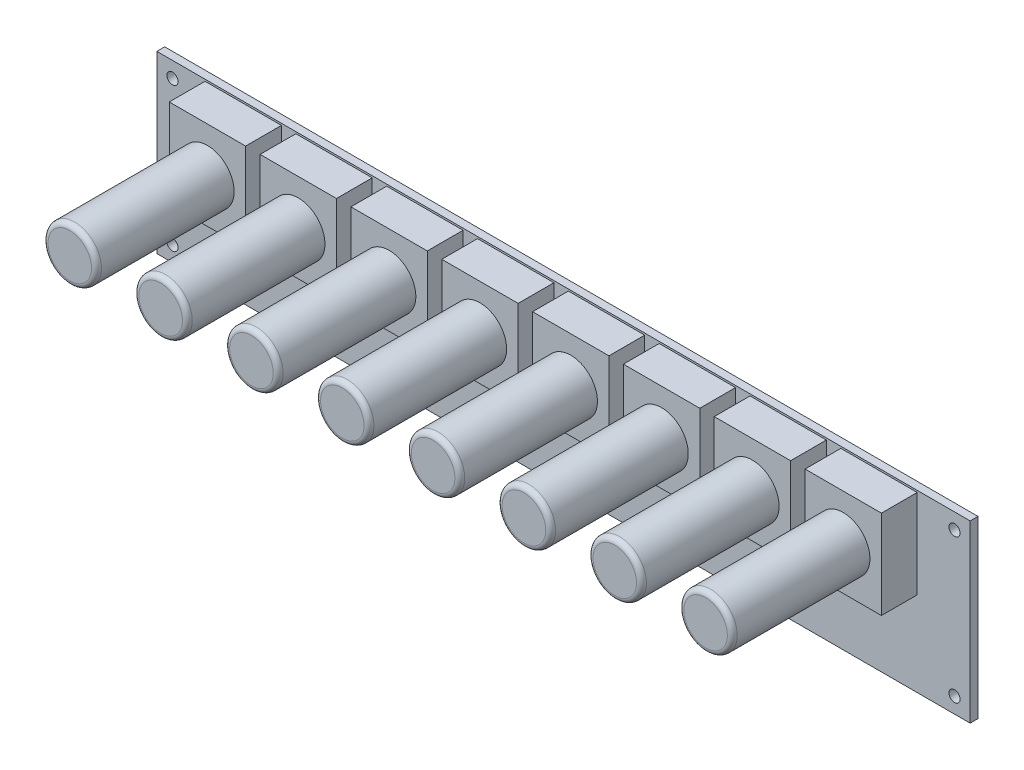
SolidWorks part; units mm, degrees
ref_plane "Front Plane" through (0, 0, 0) normal (0, 0, 1) x (1, 0, 0)
ref_plane "Top Plane" through (0, 0, 0) normal (0, 1, 0) x (1, 0, 0)
ref_plane "Right Plane" through (0, 0, 0) normal (1, 0, 0) x (0, 0, -1)
sketch "Sketch1" plane through (0, 0, 0) normal (0, 0, 1) x (1, 0, 0)
  line L0 (0, 0) -> (0, 35.56)
  line L1 (0, 35.56) -> (165.1, 35.56)
  line L2 (165.1, 35.56) -> (165.1, 0)
  line L3 (165.1, 0) -> (0, 0)
extrude "BOARD" add sketch "Sketch1" along normal blind 1.5921 separate body
ref_plane "Plane1" through (0, 0, 1.5921) normal (0, 0, 1) x (1, 0, 0)
sketch "Sketch2" plane through (0, 0, 0) normal (0, 0, 1) x (1, 0, 0)
  line L0 (87.2363, 8.7884) -> (87.2363, 15.3924)
  line L1 (87.2363, 15.3924) -> (100.4443, 15.3924)
  line L2 (100.4443, 15.3924) -> (100.4443, 8.7884)
  line L3 (100.4443, 8.7884) -> (87.2363, 8.7884)
extrude "CONN-AMP-2X5PIN-100MIL-ST-1" add sketch "Sketch2" against normal blind 8.636 separate body
sketch "Sketch3" plane through (0, 0, 0) normal (0, 0, 1) x (1, 0, 0)
  line L0 (19.6977, 9.271) -> (19.6977, 15.875)
  line L1 (19.6977, 15.875) -> (32.9057, 15.875)
  line L2 (32.9057, 15.875) -> (32.9057, 9.271)
  line L3 (32.9057, 9.271) -> (19.6977, 9.271)
extrude "CONN-AMP-2X5PIN-100MIL-ST-2" add sketch "Sketch3" against normal blind 8.636 separate body
sketch "Sketch4" plane through (0, 0, 1.5921) normal (0, 0, 1) x (1, 0, 0)
  line L0 (154.3513, 17.1874) -> (138.8512, 17.1874)
  line L1 (138.8512, 17.1874) -> (138.8512, 35.1874)
  line L2 (138.8512, 35.1874) -> (154.3513, 35.1874)
  line L3 (154.3513, 35.1874) -> (154.3513, 17.1874)
extrude "SWITCH-EC11E15244-1" add sketch "Sketch4" along normal blind 7.2644 separate body
sketch "Sketch5" plane through (0, 0, 1.5921) normal (0, 0, 1) x (1, 0, 0)
  line L0 (135.9137, 17.1874) -> (120.4137, 17.1874)
  line L1 (120.4137, 17.1874) -> (120.4137, 35.1874)
  line L2 (120.4137, 35.1874) -> (135.9137, 35.1874)
  line L3 (135.9137, 35.1874) -> (135.9137, 17.1874)
extrude "SWITCH-EC11E15244-2" add sketch "Sketch5" along normal blind 7.2644 separate body
sketch "Sketch6" plane through (0, 0, 1.5921) normal (0, 0, 1) x (1, 0, 0)
  line L0 (117.4762, 17.1874) -> (101.9762, 17.1874)
  line L1 (101.9762, 17.1874) -> (101.9762, 35.1874)
  line L2 (101.9762, 35.1874) -> (117.4762, 35.1874)
  line L3 (117.4762, 35.1874) -> (117.4762, 17.1874)
extrude "SWITCH-EC11E15244-3" add sketch "Sketch6" along normal blind 7.2644 separate body
sketch "Sketch7" plane through (0, 0, 1.5921) normal (0, 0, 1) x (1, 0, 0)
  line L0 (99.0387, 17.1874) -> (83.5387, 17.1874)
  line L1 (83.5387, 17.1874) -> (83.5387, 35.1874)
  line L2 (83.5387, 35.1874) -> (99.0387, 35.1874)
  line L3 (99.0387, 35.1874) -> (99.0387, 17.1874)
extrude "SWITCH-EC11E15244-4" add sketch "Sketch7" along normal blind 7.2644 separate body
sketch "Sketch8" plane through (0, 0, 1.5921) normal (0, 0, 1) x (1, 0, 0)
  line L0 (80.6012, 17.1874) -> (65.1012, 17.1874)
  line L1 (65.1012, 17.1874) -> (65.1012, 35.1874)
  line L2 (65.1012, 35.1874) -> (80.6012, 35.1874)
  line L3 (80.6012, 35.1874) -> (80.6012, 17.1874)
extrude "SWITCH-EC11E15244-5" add sketch "Sketch8" along normal blind 7.2644 separate body
sketch "Sketch9" plane through (0, 0, 1.5921) normal (0, 0, 1) x (1, 0, 0)
  line L0 (62.1637, 17.1874) -> (46.6637, 17.1874)
  line L1 (46.6637, 17.1874) -> (46.6637, 35.1874)
  line L2 (46.6637, 35.1874) -> (62.1637, 35.1874)
  line L3 (62.1637, 35.1874) -> (62.1637, 17.1874)
extrude "SWITCH-EC11E15244-6" add sketch "Sketch9" along normal blind 7.2644 separate body
sketch "Sketch10" plane through (0, 0, 1.5921) normal (0, 0, 1) x (1, 0, 0)
  line L0 (43.7262, 17.1874) -> (28.2262, 17.1874)
  line L1 (28.2262, 17.1874) -> (28.2262, 35.1874)
  line L2 (28.2262, 35.1874) -> (43.7262, 35.1874)
  line L3 (43.7262, 35.1874) -> (43.7262, 17.1874)
extrude "SWITCH-EC11E15244-7" add sketch "Sketch10" along normal blind 7.2644 separate body
sketch "Sketch11" plane through (0, 0, 1.5921) normal (0, 0, 1) x (1, 0, 0)
  line L0 (25.2887, 17.1874) -> (9.7887, 17.1874)
  line L1 (9.7887, 17.1874) -> (9.7887, 35.1874)
  line L2 (9.7887, 35.1874) -> (25.2887, 35.1874)
  line L3 (25.2887, 35.1874) -> (25.2887, 17.1874)
extrude "SWITCH-EC11E15244-8" add sketch "Sketch11" along normal blind 7.2644 separate body
sketch "Sketch12" plane through (0, 0, 8.8565) normal (0, 0, 1) x (1, 0, 0)
  line L0 (165.1, 35.56) -> (0, 35.56) construction
  circle A0 centre (17.5387, 26) radius 5.42
  dimension "D1" = 10.84
  dimension "D2" = 9.56
extrude "Boss-Extrude12" add sketch "Sketch12" along normal blind 27.94
fillet "Fillet2" radius 1 1 edges at (22.9587, 26, 36.7965)
pattern_linear "LPattern1" count 8 spacing 18.4375 along (1, 0, 0) of "Boss-Extrude12", "Fillet2"
sketch "Sketch13" plane through (0, 0, 1.5921) normal (0, 0, 1) x (1, 0, 0)
  line L0 (0, 35.56) -> (0, 0) construction
  line L1 (165.1, 35.56) -> (0, 35.56) construction
  line L2 (0, 0) -> (165.1, 0) construction
  line L3 (165.1, 0) -> (165.1, 35.56) construction
  circle A0 centre (3.175, 32.385) radius 1.1303
  circle A1 centre (3.175, 3.175) radius 1.1303
  circle A2 centre (161.925, 3.175) radius 1.1303
  circle A3 centre (161.925, 32.385) radius 1.1303
  dimension "D1" = 2.2606
  dimension "D4" = 2.2606
  dimension "D7" = 2.2606
  dimension "D8" = 2.2606
  dimension "D2" = 3.175
  dimension "D3" = 3.175
  dimension "D5" = 3.175
  dimension "D6" = 3.175
  dimension "D9" = 3.175
  dimension "D10" = 3.175
  dimension "D11" = 3.175
  dimension "D12" = 3.175
extrude "Cut-Extrude1" cut sketch "Sketch13" against normal blind 2.54
